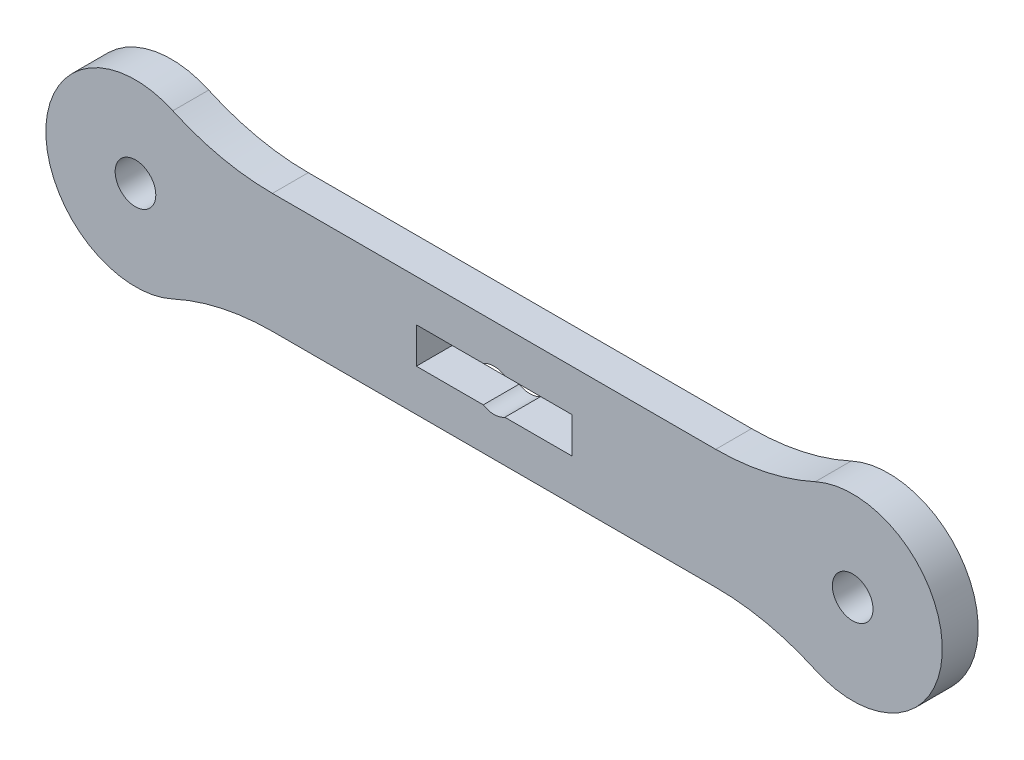
SolidWorks part; units mm, degrees
ref_plane "Plano frontal" through (0, 0, 0) normal (0, 0, 1) x (1, 0, 0)
ref_plane "Plano superior" through (0, 0, 0) normal (0, 1, 0) x (1, 0, 0)
ref_plane "Plano direito" through (0, 0, 0) normal (1, 0, 0) x (0, 0, -1)
sketch "Esboço1" plane through (0, 0, 0) normal (0, 0, 1) x (1, 0, 0)
  line L0 (5.5902, -5) -> (54.4098, -5)
  line L1 (0, 0) -> (60, 0) construction
  line L2 (5.5902, 5) -> (54.4098, 5)
  line L3 (0, 5) -> (80, 5) construction
  line L4 (0, -5) -> (80, -5) construction
  line L5 (30, 5) -> (30, -5) construction
  line L6 (30.9014, -1.5) -> (36.5, -1.5)
  line L7 (0, 0) -> (80, 0) construction
  line L8 (23.5, 1.5) -> (29.0986, 1.5)
  line L9 (23.5, 1.5) -> (23.5, -1.5)
  line L10 (23.5, -1.5) -> (29.0986, -1.5)
  line L11 (36.5, 1.5) -> (36.5, -1.5)
  line L12 (23.5, 1.5) -> (36.5, -1.5) construction
  line L13 (23.5, -1.5) -> (36.5, 1.5) construction
  line L14 (30.9014, 1.5) -> (36.5, 1.5)
  circle A0 centre (0, 0) radius 1.7
  circle A2 centre (0, 0) radius 1.7
  arc A3 (5.5902, 5) -> (5.5902, -5) centre (0, 0) ccw
  arc A4 (29.0986, -1.5) -> (30.9014, -1.5) centre (30, 0) ccw
  circle A5 centre (0, 0) radius 1.7
  arc A6 (30.9014, 1.5) -> (29.0986, 1.5) centre (30, 0) ccw
  circle A8 centre (0, 0) radius 1.7
  circle A9 centre (60, 0) radius 1.7
  circle A11 centre (0, 0) radius 1.7
  circle A13 centre (0, 0) radius 1.7
  circle A16 centre (60, 0) radius 1.7
  circle A18 centre (60, 0) radius 1.7
  circle A20 centre (60, 0) radius 1.7
  arc A22 (54.4098, 5) -> (54.4098, -5) centre (60, 0) cw
  circle A23 centre (60, 0) radius 1.7
  circle A25 centre (60, 0) radius 1.7
  point P2 (30, 0)
  point P14 (30, 0)
  point P32 (0, 0)
  dimension "D1" = 3.4
  dimension "D3" = 1.75
  dimension "D4" = 3
  dimension "D6" = 6
  dimension "D8" = 15
  dimension "D2" = 5
  dimension "D5" = 5
  dimension "D7" = 30
  dimension "D9" = 13
extrude "Ressalto-extrusão1" add sketch "Esboço1" along normal blind 3
fillet "Filete1" radius 20 4 edges at (5.5902, -5, 1.5) (54.4098, -5, 1.5) (54.4098, 5, 1.5) (5.5902, 5, 1.5)
